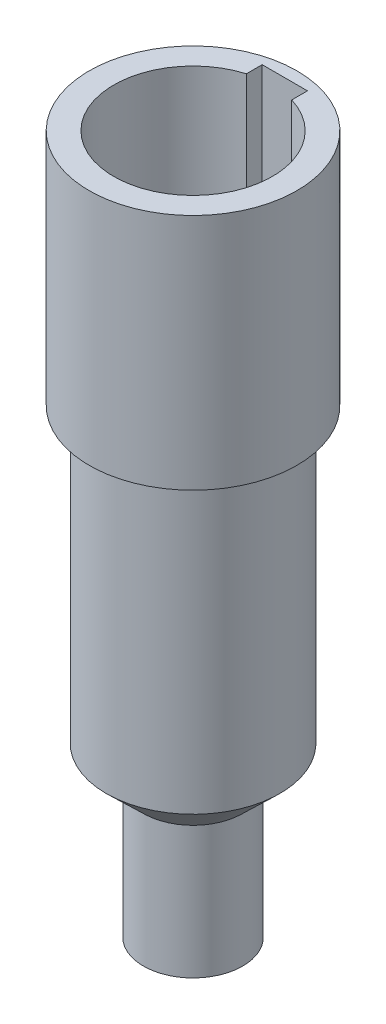
SolidWorks part; units mm, degrees
ref_plane "Front Plane" through (0, 0, 0) normal (0, 0, 1) x (1, 0, 0)
ref_plane "Top Plane" through (0, 0, 0) normal (0, 1, 0) x (1, 0, 0)
ref_plane "Right Plane" through (0, 0, 0) normal (1, 0, 0) x (0, 0, -1)
sketch "Sketch1" plane through (0, 0, 0) normal (0, 0, 1) x (1, 0, 0)
  line L0 (0, 0) -> (0, 189.985) construction
  line L1 (0, 0) -> (-13.15, 0)
  line L2 (-13.15, 0) -> (-13.15, 35)
  line L3 (-13.15, 35) -> (-23, 44.5)
  line L4 (-23, 44.5) -> (-23, 122)
  line L5 (-23, 122) -> (-27.5, 122)
  line L6 (-27.5, 122) -> (-27.5, 185)
  line L7 (-27.5, 185) -> (-11, 185)
  line L8 (-11, 185) -> (-11, 145)
  line L9 (-11, 145) -> (0, 145)
  line L10 (0, 145) -> (0, 0)
  dimension "D1" = 185
  dimension "D2" = 55
  dimension "D3" = 46
  dimension "D4" = 26.3
  dimension "D5" = 22
  dimension "D6" = 40
  dimension "D7" = 140.5
  dimension "D8" = 150
  dimension "D9" = 63
revolve "Revolve1" add sketch "Sketch1" angle 360 about L0
sketch "Sketch2" plane through (0, 185, 0) normal (0, 1, 0) x (1, 0, 0)
  circle A0 centre (0, 0) radius 21
  dimension "D1" = 42
extrude "Cut-Extrude1" cut sketch "Sketch2" against normal blind 57
sketch "Sketch3" plane through (0, 185, 0) normal (0, 1, 0) x (1, 0, 0)
  line L0 (0, 16) -> (0, 0) construction
  line L1 (6, 16) -> (-6, 16)
  line L2 (6, 16) -> (6, 24.3)
  line L3 (6, 24.3) -> (-6, 24.3)
  line L4 (-6, 16) -> (-6, 24.3)
  dimension "D1" = 16
  dimension "D2" = 24.3
  dimension "D3" = 12
extrude "Cut-Extrude2" cut sketch "Sketch3" against normal up to surface (57 mm away) up to face at (0, 128, 21)
